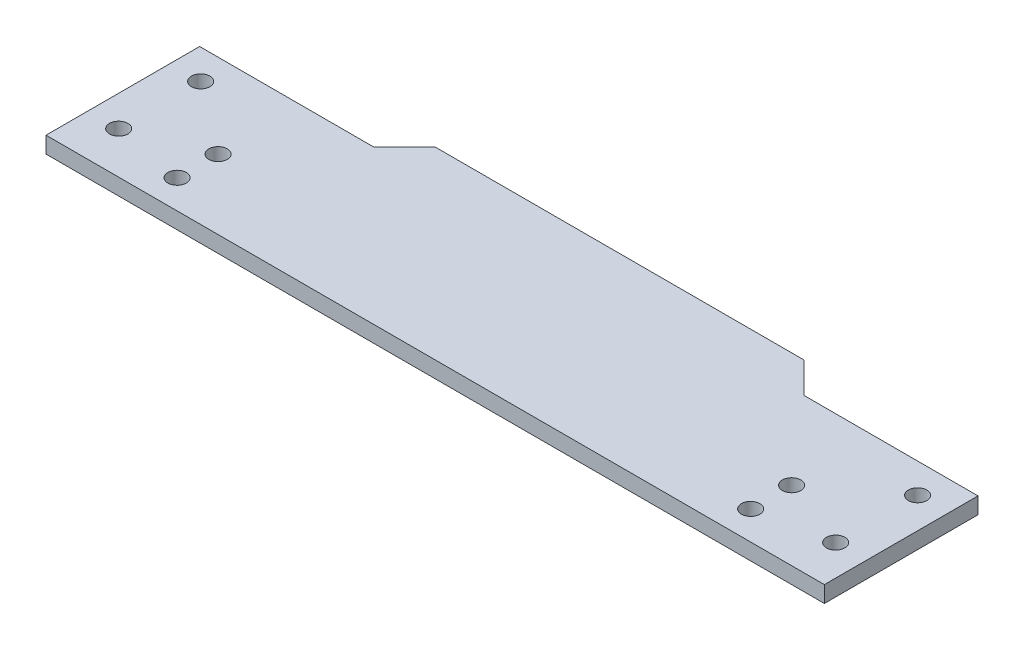
SolidWorks part; units mm, degrees
ref_plane "Plan de face" through (0, 0, 0) normal (0, 0, 1) x (1, 0, 0)
ref_plane "Plan de dessus" through (0, 0, 0) normal (0, 1, 0) x (1, 0, 0)
ref_plane "Plan de droite" through (0, 0, 0) normal (1, 0, 0) x (0, 0, -1)
sketch "Esquisse1" plane through (0, 0, 0) normal (0, 1, 0) x (1, 0, 0)
  line L0 (-190, 0) -> (190, 0)
  line L1 (190, 0) -> (190, 75)
  line L2 (190, 75) -> (105, 75)
  line L3 (105, 75) -> (90, 90)
  line L4 (90, 90) -> (-90, 90)
  line L5 (0, 90) -> (0, 0)
  line L6 (105, 75) -> (55.7702, 75) construction
  line L7 (-105, 75) -> (-55.7702, 75) construction
  line L8 (-105, 75) -> (-90, 90)
  line L9 (-190, 75) -> (-105, 75)
  line L10 (-190, 0) -> (-190, 75)
  circle A0 centre (140, 14) radius 4.5
  circle A1 centre (140, 34) radius 4.5
  circle A2 centre (175, 20.5) radius 4.5
  circle A3 centre (175, 60.5) radius 4.5
  circle A4 centre (-175, 60.5) radius 4.5
  circle A5 centre (-175, 20.5) radius 4.5
  circle A6 centre (-140, 34) radius 4.5
  circle A7 centre (-140, 14) radius 4.5
  dimension "D6" = 9
  dimension "D9" = 9
  dimension "D12" = 9
  dimension "D14" = 9
  dimension "D11" = 140
  dimension "D1" = 190
  dimension "D2" = 75
  dimension "D3" = 85
  dimension "D4" = 45
  dimension "D5" = 90
  dimension "D7" = 14
  dimension "D8" = 140
  dimension "D10" = 20
  dimension "D13" = 20.5
  dimension "D15" = 15
  dimension "D16" = 40
  dimension "D17" = 15
extrude "Boss.-Extru.1" add sketch "Esquisse1" along normal blind 8 contours L10 L0 L5 L4 L8 L9 A6 A4 A5 A7 | L4 L5 L0 L1 L2 L3 A3 A2 A1 A0
